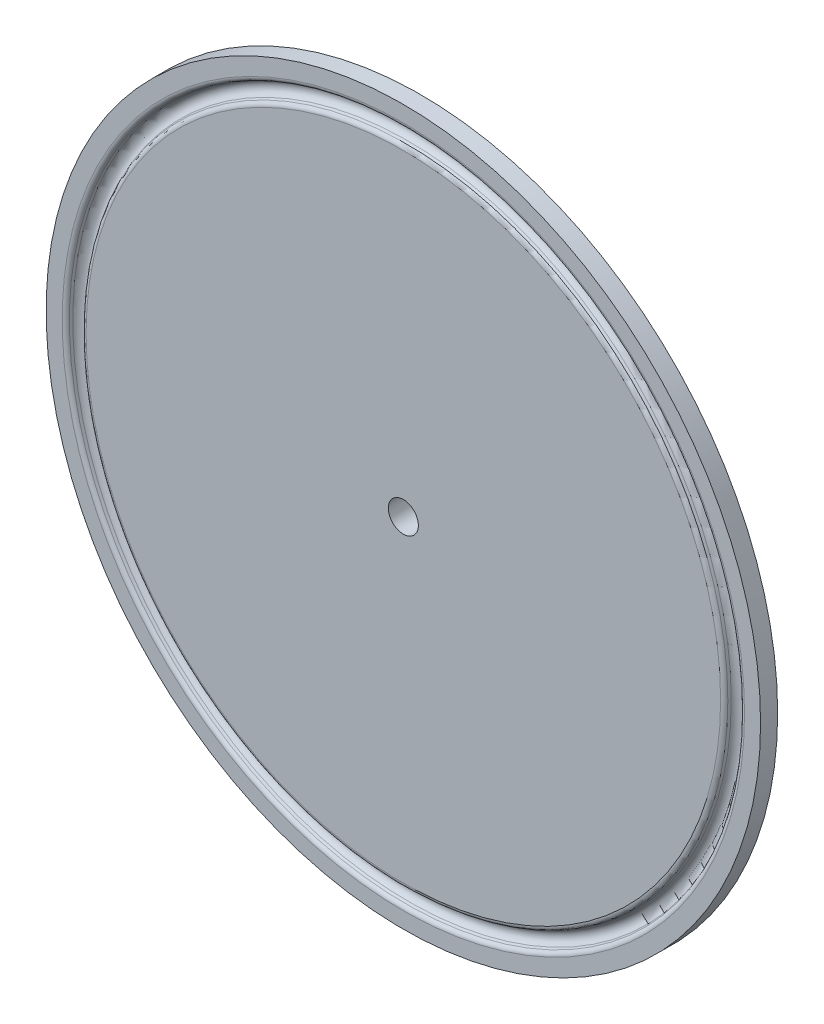
SolidWorks part; units mm, degrees
ref_plane "Front Plane" through (0, 0, 0) normal (0, 0, 1) x (1, 0, 0)
ref_plane "Top Plane" through (0, 0, 0) normal (0, 1, 0) x (1, 0, 0)
ref_plane "Right Plane" through (0, 0, 0) normal (1, 0, 0) x (0, 0, -1)
sketch "Sketch1" plane through (0, 0, 0) normal (1, 0, 0) x (0, 0, -1)
  line L0 (0, 0) -> (7.9248, 0) construction
  line L1 (0, 0) -> (0, 52.8099)
  line L2 (0, 59.4614) -> (2.8448, 59.4614)
  line L3 (2.8448, 59.4614) -> (7.9248, 45.5042)
  line L4 (7.9248, 45.5042) -> (7.9248, 0)
  line L5 (0, 56.7911) -> (0, 59.4614)
  line L6 (0.4797, 56.0663) -> (0.8729, 55.8994)
  line L7 (0.4797, 53.5347) -> (0.8729, 53.7016)
  line L8 (0, 56.2699) -> (0, 53.3311) construction
  line L9 (0, 54.8005) -> (0.4064, 54.8005) construction
  line L10 (0, 0) -> (7.9248, 0)
  arc A0 (0.8729, 53.7016) -> (0.8729, 55.8994) centre (0.4064, 54.8005) ccw
  arc A2 (0, 52.8099) -> (0.4797, 53.5347) centre (0.7874, 52.8099) cw
  arc A3 (0, 56.7911) -> (0.4797, 56.0663) centre (0.7874, 56.7911) ccw
  dimension "K" = 1.1938
  dimension "L" = 0.7874
  dimension "I" = 20
  dimension "C" = 91.0084
  dimension "F" = 2.8448
  dimension "H" = 0.4064
  dimension "B" = 109.601
  dimension "A" = 118.9228
  dimension "M" = 46
  dimension "N" = 23
  dimension "Length" = 7.9248
revolve "Revolve1" add sketch "Sketch1" angle 360 about L0
sketch "Sketch2" plane through (0, 0, -7.9248) normal (0, 0, -1) x (-1, 0, 0)
  circle A0 centre (0, 0) radius 2.5
  circle A1 centre (0, 0) radius 3.5
  dimension "D1" = 5
  dimension "D2" = 7
extrude "Boss-Extrude1" add sketch "Sketch2" along normal blind 10
sketch "Sketch3" plane through (0, 0, -7.9248) normal (0, 0, -1) x (-1, 0, 0)
  circle A0 centre (0, 0) radius 2.5
extrude "Cut-Extrude1" cut sketch "Sketch3" against normal through all both and the other way through all
fillet "Fillet1" radius 2 1 edges at (3.5, 0, -7.9248)
